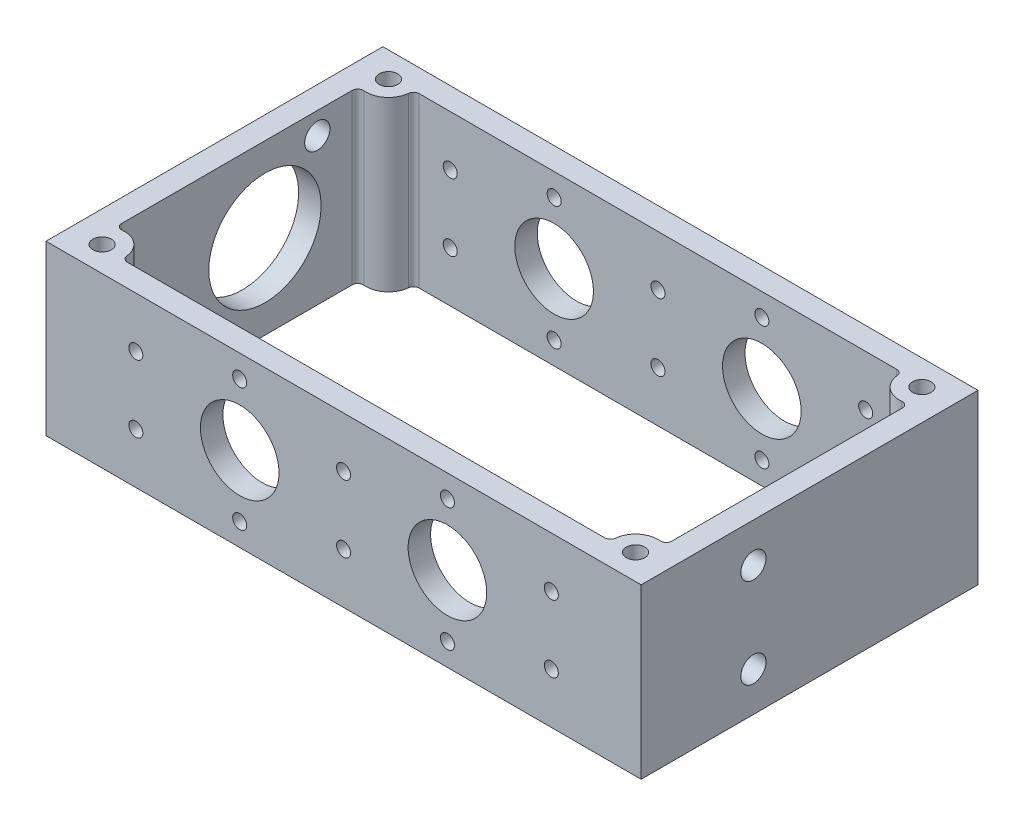
SolidWorks part; units mm, degrees
ref_plane "前视基准面" through (0, 0, 0) normal (0, 0, 1) x (1, 0, 0)
ref_plane "上视基准面" through (0, 0, 0) normal (0, 1, 0) x (1, 0, 0)
ref_plane "右视基准面" through (0, 0, 0) normal (1, 0, 0) x (0, 0, -1)
sketch "草图1" plane through (0, 0, 0) normal (0, 1, 0) x (1, 0, 0)
  line L1 (-53, -30) -> (53, -30)
  line L2 (-53, -30) -> (-53, 30)
  line L3 (-53, 30) -> (53, 30)
  line L4 (53, -30) -> (53, 30)
  line L5 (-53, -30) -> (53, 30) construction
  line L6 (-53, 30) -> (53, -30) construction
  point P0 (0, 0)
  dimension "D1" = 60
  dimension "D2" = 106
extrude "凸台-拉伸1" add sketch "草图1" along normal mid plane 30
sketch "草图4" plane through (0, 15, 0) normal (0, 1, 0) x (1, 0, 0)
  line L16 (53, 30) -> (-53, 30) construction
  line L17 (-49, -26) -> (49, -26)
  line L19 (-49, -26) -> (-49, 26)
  line L21 (-49, 26) -> (49, 26)
  line L23 (49, -26) -> (49, 26)
  line L24 (-49, -26) -> (49, 26) construction
  line L25 (-49, 26) -> (49, -26) construction
  line L27 (53, -30) -> (53, 30) construction
  point P0 (0, 0)
  dimension "D2" = 4
  dimension "D1" = 4
extrude "切除-拉伸3" cut sketch "草图4" against normal through all
sketch "草图5" plane through (0, 15, 0) normal (0, 1, 0) x (1, 0, 0)
  line L0 (0, -0.3948) -> (0, 49999.6052) construction
  line L1 (0, 0) -> (50000, 0) construction
  line L2 (53, -30) -> (53, 30) construction
  circle A0 centre (47.5, 25.5) radius 2
  dimension "D1" = 4
  dimension "D2" = 51
  dimension "D3" = 5.5
extrude "凸台-拉伸2" add sketch "草图5" against normal up to surface (30 mm away) up to face at (0, -15, 0)
mirror "镜向2" about plane through (0, 0, 0) normal (1, 0, 0) of "凸台-拉伸2"
mirror "镜向3" about plane through (0, 0, 0) normal (0, 0, 1) of "凸台-拉伸2", "镜向2"
sketch "草图3" plane through (0, 15, 0) normal (0, 1, 0) x (1, 0, 0)
  line L0 (0, 0) -> (-50000, 0) construction
  line L1 (0, 0) -> (0, 50000) construction
  line L2 (53, -30) -> (53, 30) construction
  circle A0 centre (47.5, 25.5) radius 1.65
  circle A1 centre (47.5, -25.5) radius 1.65
  circle A2 centre (-47.5, -25.5) radius 1.65
  circle A3 centre (-47.5, 25.5) radius 1.65
  dimension "D1" = 51
  dimension "D2" = 5.5
  dimension "D3" = 3.3
extrude "切除-拉伸2" cut sketch "草图3" against normal blind 10
mirror "镜向1" about plane through (0, 0, 0) normal (0, 1, 0) of "切除-拉伸2"
sketch "草图6" plane through (-53, 0, 0) normal (-1, 0, 0) x (0, 0, 1)
  line L0 (-30, 15) -> (-30, -15) construction
  line L1 (-30, -15) -> (30, -15) construction
  line L2 (-5, 0) -> (-32144.3805, 38302.2222) construction
  line L3 (-5, 0) -> (-5, 50000) construction
  circle A0 centre (-5, 0) radius 10
  circle A1 centre (-14.3204, 11.1076) radius 2.25
  circle A2 centre (4.3204, -11.1076) radius 2.25
  dimension "D1" = 20
  dimension "D2" = 25
  dimension "D3" = 15
  dimension "D5" = 29
  dimension "D6" = 14.5
  dimension "D7" = 4.5
  dimension "D4" = 40
extrude "切除-拉伸4" cut sketch "草图6" against normal up to next
sketch "草图7" plane through (49, 0, 0) normal (-1, 0, 0) x (0, 0, 1)
  line L0 (30, 15) -> (30, -15) construction
  line L1 (10, -8) -> (10, 8) construction
  line L2 (-30, -15) -> (30, -15) construction
  circle A0 centre (10, 8) radius 2.25
  circle A1 centre (10, -8) radius 2.25
  dimension "D1" = 20
  dimension "D2" = 16
  dimension "D3" = 7
  dimension "D4" = 4.5
extrude "切除-拉伸5" cut sketch "草图7" against normal through all
sketch "草图8" plane through (0, 0, 30) normal (0, 0, 1) x (1, 0, 0)
  line L0 (0, 0) -> (0, 50000) construction
  line L1 (0, 0) -> (50000, 0) construction
  line L2 (-53, -15) -> (53, -15) construction
  line L3 (53, 15) -> (53, -15) construction
  circle A0 centre (18.5, 0) radius 7
  circle A1 centre (0, 6) radius 1.5
  circle A2 centre (18.5, 11) radius 1.5
  circle A3 centre (37, 6) radius 1.5
  dimension "D1" = 15
  dimension "D2" = 37
  dimension "D3" = 14
  dimension "D4" = 11
  dimension "D5" = 12
  dimension "D6" = 16
  dimension "D7" = 34.5
  dimension "D8" = 3
extrude "切除-拉伸6" cut sketch "草图8" against normal through all contours A0
hole_wizard "M3 螺纹孔1" positions "3D草图1" profile "草图9" tap size "M3" standard "GB" end condition through all
sketch3d "3D草图1"
  point P0 (0, 6, 30)
  point P3 (18.5, 11, 30)
  point P6 (37, 6, 30)
sketch "草图9" plane through (0, 6, 30) normal (1, 0, 0) x (0, -1, 0)
  line L0 (0, 0) -> (0, 60)
  line L1 (0, 60) -> (1.25, 60)
  line L2 (1.25, 60) -> (1.25, 0)
  line L5 (1.25, 0) -> (0, 0)
  line L11 (0, -6.35) -> (0, 107.95) construction
  dimension "通孔螺纹孔钻头直径" = 2.5
  dimension "通孔螺纹孔钻头深度" = 60
cosmetic thread "孔螺纹线1" parameters "D2"=3
cosmetic thread "孔螺纹线2" parameters "D2"=3
cosmetic thread "孔螺纹线3" parameters "D2"=3
mirror "镜向4" about plane through (0, 0, 0) normal (1, 0, 0) of "切除-拉伸6", "M3 螺纹孔1" second plane through (0, 0, 0) second plane normal (0, 1, 0)
sketch "草图10" plane through (0, 15, 0) normal (0, 1, 0) x (1, 0, 0)
  line L4 (53, -30) -> (53, 30)
  line L5 (53, 30) -> (-53, 30)
  line L6 (-53, 30) -> (-53, -30)
  line L7 (-53, -30) -> (53, -30)
  line L8 (53, -30) -> (53, 30)
  line L9 (53, 30) -> (-53, 30)
  line L10 (-53, 30) -> (-53, -30)
  line L11 (-53, -30) -> (53, -30)
  circle A0 centre (-47.5, 25.5) radius 4
  circle A1 centre (-47.5, -25.5) radius 4
  circle A2 centre (47.5, -25.5) radius 4
  circle A3 centre (47.5, 25.5) radius 4
  line M12 (45.5635, -26) -> (-45.5635, -26)
  arc M13 (-45.5635, -26) -> (-49, -24.1771) centre (-47.5, -25.5) ccw
  line M14 (-49, -24.1771) -> (-49, 24.1771)
  arc M15 (-49, 24.1771) -> (-45.5635, 26) centre (-47.5, 25.5) ccw
  line M16 (-45.5635, 26) -> (45.5635, 26)
  arc M17 (45.5635, 26) -> (49, 24.1771) centre (47.5, 25.5) ccw
  line M18 (49, 24.1771) -> (49, -24.1771)
  arc M19 (49, -24.1771) -> (45.5635, -26) centre (47.5, -25.5) ccw
  dimension "D1" = 8
  dimension "D2" = 0
extrude "凸台-拉伸3" add sketch "草图10" against normal up to surface (30 mm away) contours A0 M14 M16 M15 | A1 M12 M14 M13 | A2 M18 M12 M19 | A3 M16 M18 M17
fillet "圆角1" radius 1 8 edges at (-43.5314, 0, -26) (-49, 0, -21.7919) (-49, 0, 21.7919) (-43.5314, 0, 26) (43.5314, 0, 26) (49, 0, 21.7919) (43.5314, 0, -26) (49, 0, -21.7919)
